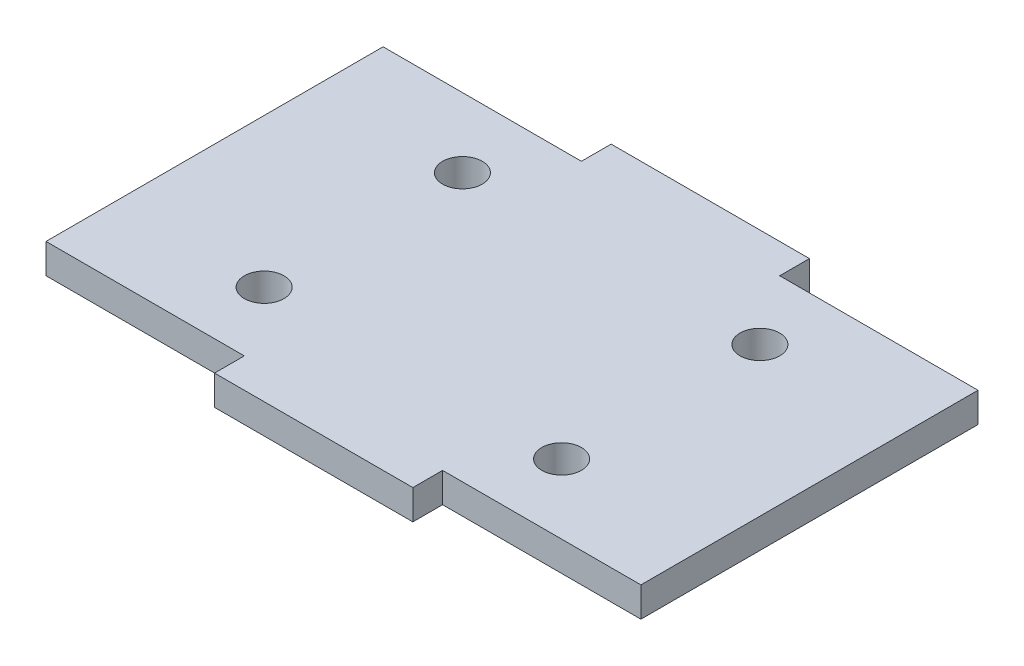
SolidWorks part; units mm, degrees
material "Acrylic (Medium-high impact)"
ref_plane "Front Plane" through (0, 0, 0) normal (0, 0, 1) x (1, 0, 0)
ref_plane "Top Plane" through (0, 0, 0) normal (0, 1, 0) x (1, 0, 0)
ref_plane "Right Plane" through (0, 0, 0) normal (1, 0, 0) x (0, 0, -1)
sketch "Sketch1" plane through (0, 0, 0) normal (0, 1, 0) x (1, 0, 0)
  line L1 (30, -20) -> (-30, -20)
  line L2 (30, -20) -> (30, 20)
  line L3 (30, 20) -> (-30, 20)
  line L4 (-30, -20) -> (-30, 20)
  line L5 (30, -20) -> (-30, 20) construction
  line L6 (30, 20) -> (-30, -20) construction
  point P0 (0, 0)
  dimension "D1" = 60
  dimension "D2" = 40
extrude "Boss-Extrude1" add sketch "Sketch1" along normal blind 3
sketch "Sketch2" plane through (0, 3, 0) normal (0, 1, 0) x (1, 0, 0)
  line L0 (-30, -20) -> (30, -20) construction
  line L1 (-10, -23) -> (-30, -23)
  line L2 (-10, -23) -> (-10, -17)
  line L3 (-10, -17) -> (-30, -17)
  line L4 (-30, -23) -> (-30, -17)
  line L5 (-10, -23) -> (-30, -17) construction
  line L6 (-10, -17) -> (-30, -23) construction
  line L7 (-30, 20) -> (-30, -20) construction
  line L8 (0, 20) -> (0, -20) construction
  line L9 (30, 20) -> (-30, 20) construction
  line L10 (-30, 0) -> (30, 0) construction
  line L11 (30, -20) -> (30, 20) construction
  line L12 (10, -23) -> (30, -23)
  line L13 (30, -23) -> (30, -17)
  line L14 (10, -17) -> (30, -17)
  line L15 (10, -23) -> (10, -17)
  line L16 (30, 23) -> (30, 17)
  line L17 (10, 23) -> (30, 23)
  line L18 (10, 23) -> (10, 17)
  line L19 (10, 17) -> (30, 17)
  line L20 (-30, 23) -> (-30, 17)
  line L21 (-10, 23) -> (-30, 23)
  line L22 (-10, 23) -> (-10, 17)
  line L23 (-10, 17) -> (-30, 17)
  point P0 (-20, -20)
  dimension "D1" = 6
  dimension "D2" = 20
extrude "Cut-Extrude1" cut sketch "Sketch2" against normal blind 3
sketch "Sketch3" plane through (0, 3, 0) normal (0, 1, 0) x (1, 0, 0)
  line L0 (0, 20) -> (0, -20) construction
  line L1 (10, 20) -> (-10, 20) construction
  line L2 (-10, -20) -> (10, -20) construction
  line L3 (-30, 0) -> (30, 0) construction
  line L4 (-30, 17) -> (-30, -17) construction
  line L5 (30, -17) -> (30, 17) construction
  circle A0 centre (-15, 10) radius 2
  circle A1 centre (-15, -10) radius 2
  circle A2 centre (15, -10) radius 2
  circle A3 centre (15, 10) radius 2
  dimension "D1" = 4
  dimension "D2" = 15
  dimension "D3" = 10
extrude "Cut-Extrude2" cut sketch "Sketch3" against normal blind 3
